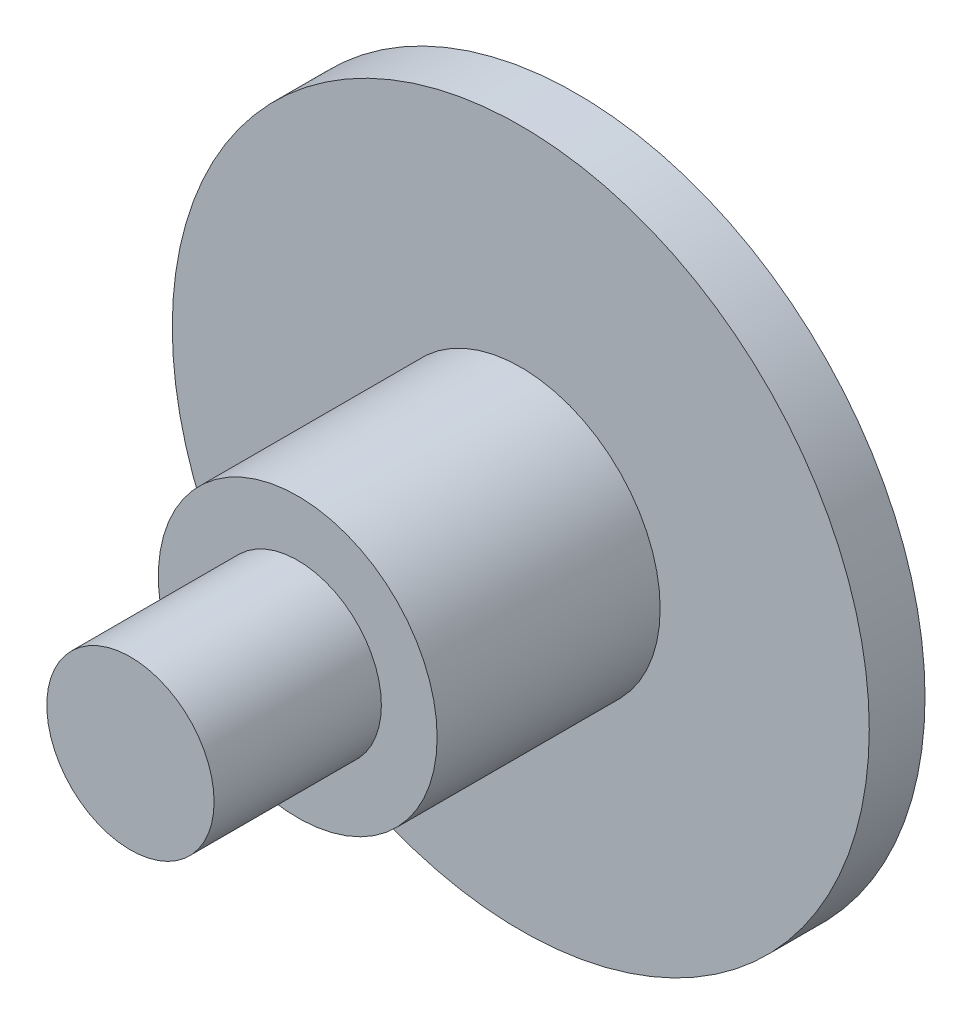
SolidWorks part; units mm, degrees
ref_plane "Front Plane" through (0, 0, 0) normal (0, 0, 1) x (1, 0, 0)
ref_plane "Top Plane" through (0, 0, 0) normal (0, 1, 0) x (1, 0, 0)
ref_plane "Right Plane" through (0, 0, 0) normal (1, 0, 0) x (0, 0, -1)
sketch "Sketch1" plane through (0, 0, 0) normal (0, 0, 1) x (1, 0, 0)
  circle A0 centre (0, 0) radius 12.5
  dimension "D1" = 25
extrude "Boss-Extrude1" add sketch "Sketch1" along normal blind 2
sketch "Sketch2" plane through (0, 0, 2) normal (0, 0, 1) x (1, 0, 0)
  circle A0 centre (0, 0) radius 3
  dimension "D1" = 6
extrude "Boss-Extrude2" add sketch "Sketch2" along normal blind 14
sketch "Sketch3" plane through (0, 0, 2) normal (0, 0, 1) x (1, 0, 0)
  circle A0 centre (0, 0) radius 5
  dimension "D1" = 10
extrude "Boss-Extrude3" add sketch "Sketch3" along normal blind 8
